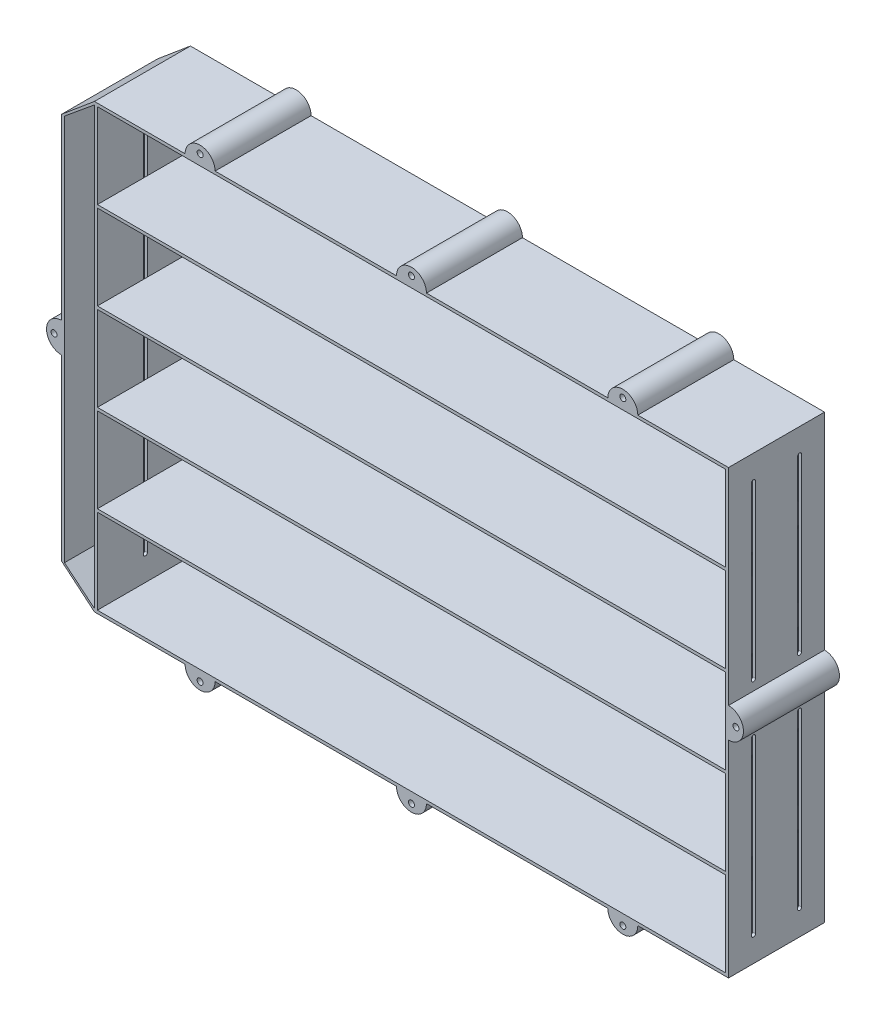
SolidWorks part; units mm, degrees
ref_plane "Front Plane" through (0, 0, 0) normal (0, 0, 1) x (1, 0, 0)
ref_plane "Top Plane" through (0, 0, 0) normal (0, 1, 0) x (1, 0, 0)
ref_plane "Right Plane" through (0, 0, 0) normal (1, 0, 0) x (0, 0, -1)
sketch "Sketch1" plane through (0, 0, 0) normal (0, 0, 1) x (1, 0, 0)
  line L0 (0, 0) -> (0, 206.5)
  line L1 (0, 443) -> (-90.9, 443)
  line L2 (-635.4, 443) -> (-668.4, 415.3097)
  line L3 (-668.4, 415.3097) -> (-668.4, 236.5)
  line L4 (-668.4, 27.6903) -> (-635.4, 0)
  line L5 (-635.4, 0) -> (-544.5, 0)
  line L6 (-544.5, 443) -> (-635.4, 443)
  line L7 (-332.7, 443) -> (-514.5, 443)
  line L8 (-120.9, 443) -> (-302.7, 443)
  line L9 (-529.5, 443) -> (-529.5, 0) construction
  line L10 (-317.7, 443) -> (-317.7, 0) construction
  line L11 (-105.9, 443) -> (-105.9, 0) construction
  line L12 (-514.5, 0) -> (-332.7, 0)
  line L13 (-302.7, 0) -> (-120.9, 0)
  line L14 (-90.9, 0) -> (0, 0)
  line L15 (-668.4, 206.5) -> (-668.4, 27.6903)
  line L16 (0, 236.5) -> (0, 443)
  line L17 (-529.5, 450.5) -> (-105.9, 450.5) construction
  line L18 (-529.5, -7.5) -> (-105.9, -7.5) construction
  arc A0 (-544.5, 443) -> (-514.5, 443) centre (-529.5, 443) cw
  arc A1 (-332.7, 443) -> (-302.7, 443) centre (-317.7, 443) cw
  arc A2 (-120.9, 443) -> (-90.9, 443) centre (-105.9, 443) cw
  arc A3 (-332.7, 0) -> (-302.7, 0) centre (-317.7, 0) ccw
  arc A4 (-544.5, 0) -> (-514.5, 0) centre (-529.5, 0) ccw
  arc A5 (-120.9, 0) -> (-90.9, 0) centre (-105.9, 0) ccw
  arc A6 (-668.4, 236.5) -> (-668.4, 206.5) centre (-668.4, 221.5) ccw
  arc A7 (0, 236.5) -> (0, 206.5) centre (0, 221.5) cw
  circle A8 centre (-529.5, 450.5) radius 3
  circle A9 centre (-317.7, 450.5) radius 3
  circle A10 centre (-105.9, 450.5) radius 3
  circle A11 centre (7.5, 221.5) radius 3
  circle A12 centre (-675.9, 221.5) radius 3
  circle A13 centre (-529.5, -7.5) radius 3
  circle A14 centre (-317.7, -7.5) radius 3
  circle A15 centre (-105.9, -7.5) radius 3
  dimension "D5" = 15
  dimension "D9" = 15
  dimension "D10" = 15
  dimension "D11" = 15
  dimension "D12" = 6
  dimension "D13" = 6
  dimension "D14" = 6
  dimension "D16" = 6
  dimension "D18" = 6
  dimension "D20" = 6
  dimension "D22" = 6
  dimension "D23" = 6
  dimension "D1" = 443
  dimension "D2" = 635.4
  dimension "D3" = 33
  dimension "D4" = 140
  dimension "D6" = 211.8
  dimension "D7" = 211.8
  dimension "D8" = 423.6
  dimension "D15" = 7.5
  dimension "D17" = 7.5
  dimension "D19" = 7.5
  dimension "D21" = 7.5
  dimension "D24" = 140
extrude "Boss-Extrude1" add sketch "Sketch1" along normal blind 96.2
sketch "Sketch2" plane through (0, 0, 96.2) normal (0, 0, 1) x (1, 0, 0)
  line L0 (-635.4, 443) -> (-635.4, 0) construction
  line L1 (-632.4, 440) -> (-3, 440)
  line L2 (-3, 440) -> (-3, 355)
  line L3 (-3, 355) -> (-632.4, 355)
  line L4 (-632.4, 355) -> (-632.4, 440)
  line L5 (0, 0) -> (0, 206.5) construction
  line L6 (0, 443) -> (-90.9, 443) construction
  line L8 (-544.5, 443) -> (-635.4, 443) construction
  dimension "D1" = 3
  dimension "D2" = 3
  dimension "D3" = 3
  dimension "D4" = 85
extrude "Cut-Extrude1" cut sketch "Sketch2" against normal blind 93.2
pattern_linear "LPattern1" count 5 spacing 88 along (0, -1, 0) of "Cut-Extrude1"
sketch "Sketch5" plane through (0, 0, 96.2) normal (0, 0, 1) x (1, 0, 0)
  line L0 (-665.4, 415.3097) -> (-665.4, 27.6903)
  line L1 (-668.4, 415.3097) -> (-668.4, 236.5) construction
  line L2 (-635.4, 3) -> (-635.4, 440)
  line L3 (-635.4, 3) -> (-665.4, 27.6903)
  line L4 (-665.4, 415.3097) -> (-635.4, 440)
  dimension "D1" = 3
  dimension "D2" = 3
extrude "Cut-Extrude3" cut sketch "Sketch5" against normal blind 93.2
ref_plane "MidPlane" through (0, 221.5, 0) normal (0, 1, 0) x (1, 0, 0)
sketch "Sketch6" plane through (0, 440, 0) normal (0, -1, 0) x (1, 0, 0)
  line L0 (-3, 18) -> (-3, 3)
  arc A0 (-3, 3) -> (-3, 18) centre (-3, 10.5) cw
  dimension "D1" = 3
  dimension "D2" = 3
  dimension "D3" = 15
sketch "Sketch7" plane through (0, 0, 0) normal (1, 0, 0) x (0, 0, -1)
  line L0 (-71.2, 418) -> (-71.2, 246.5) construction
  line L1 (-69.2, 418) -> (-69.2, 246.5)
  line L2 (-73.2, 418) -> (-73.2, 246.5)
  line L3 (-25, 418) -> (-25, 246.5) construction
  line L4 (-23, 418) -> (-23, 246.5)
  line L5 (-27, 418) -> (-27, 246.5)
  line L6 (-96.2, 443) -> (0, 443) construction
  line L7 (0, 443) -> (0, 0) construction
  line L8 (0, 0) -> (-96.2, 0) construction
  line L9 (-96.2, 0) -> (-96.2, 443) construction
  line L10 (-71.2, 246.5) -> (-71.2, 25) construction
  line L11 (-25, 246.5) -> (-25, 25) construction
  line L12 (-71.2, 196.5) -> (-71.2, 25) construction
  line L13 (-69.2, 196.5) -> (-69.2, 25)
  line L14 (-73.2, 196.5) -> (-73.2, 25)
  line L15 (-25, 196.5) -> (-25, 25) construction
  line L16 (-23, 196.5) -> (-23, 25)
  line L17 (-27, 196.5) -> (-27, 25)
  arc A0 (-69.2, 418) -> (-73.2, 418) centre (-71.2, 418) ccw
  arc A1 (-73.2, 246.5) -> (-69.2, 246.5) centre (-71.2, 246.5) ccw
  arc A2 (-23, 418) -> (-27, 418) centre (-25, 418) ccw
  arc A3 (-27, 246.5) -> (-23, 246.5) centre (-25, 246.5) ccw
  arc A4 (-69.2, 196.5) -> (-73.2, 196.5) centre (-71.2, 196.5) ccw
  arc A5 (-73.2, 25) -> (-69.2, 25) centre (-71.2, 25) ccw
  arc A6 (-23, 196.5) -> (-27, 196.5) centre (-25, 196.5) ccw
  arc A7 (-27, 25) -> (-23, 25) centre (-25, 25) ccw
  point P2 (-71.2, 332.25)
  point P9 (-25, 332.25)
  point P23 (-71.2, 110.75)
  point P34 (-25, 110.75)
  dimension "D3" = 2
  dimension "D4" = 25
  dimension "D7" = 2
  dimension "D1" = 25
  dimension "D2" = 10
  dimension "D5" = 25
  dimension "D6" = 25
  dimension "D8" = 10
extrude "Cut-Extrude4" cut sketch "Sketch7" against normal up to surface (3 mm away) up to face at (-3, 397.5, 49.6)
sketch "Sketch8" plane through (-635.4, 0, 0) normal (-1, 0, 0) x (0, 0, 1)
  line L0 (48.1, 28) -> (48.1, 415) construction
  line L2 (96.2, 27.6903) -> (0, 27.6903) construction
  line L3 (48.1, 415) -> (48.1, 28) construction
  line L4 (50.1, 415) -> (50.1, 28)
  line L5 (46.1, 415) -> (46.1, 28)
  arc A0 (50.1, 415) -> (46.1, 415) centre (48.1, 415) ccw
  arc A1 (46.1, 28) -> (50.1, 28) centre (48.1, 28) ccw
  point P2 (48.1, 221.5)
  point P5 (48.1, 27.6903)
  dimension "D3" = 2
  dimension "D1" = 25
  dimension "D2" = 25
extrude "Cut-Extrude5" cut sketch "Sketch8" against normal up to surface (3 mm away) up to face at (-632.4, 397.5, 49.6)
sketch "Sketch9" plane through (-668.4, 0, 0) normal (-1, 0, 0) x (0, 0, 1)
  line L0 (48.1, 390.3097) -> (48.1, 52.6903) construction
  line L1 (96.2, 415.3097) -> (0, 415.3097) construction
  line L2 (96.2, 27.6903) -> (0, 27.6903) construction
  line L3 (48.1, 390.3097) -> (48.1, 52.6903) construction
  line L4 (50.1, 390.3097) -> (50.1, 52.6903)
  line L5 (46.1, 390.3097) -> (46.1, 52.6903)
  arc A0 (50.1, 390.3097) -> (46.1, 390.3097) centre (48.1, 390.3097) ccw
  arc A1 (46.1, 52.6903) -> (50.1, 52.6903) centre (48.1, 52.6903) ccw
  point P6 (48.1, 27.6903)
  point P7 (48.1, 221.5)
  dimension "D3" = 2
  dimension "D1" = 25
  dimension "D2" = 25
extrude "Cut-Extrude6" cut sketch "Sketch9" against normal up to surface (3 mm away) up to face at (-665.4, 221.5, 49.6)
